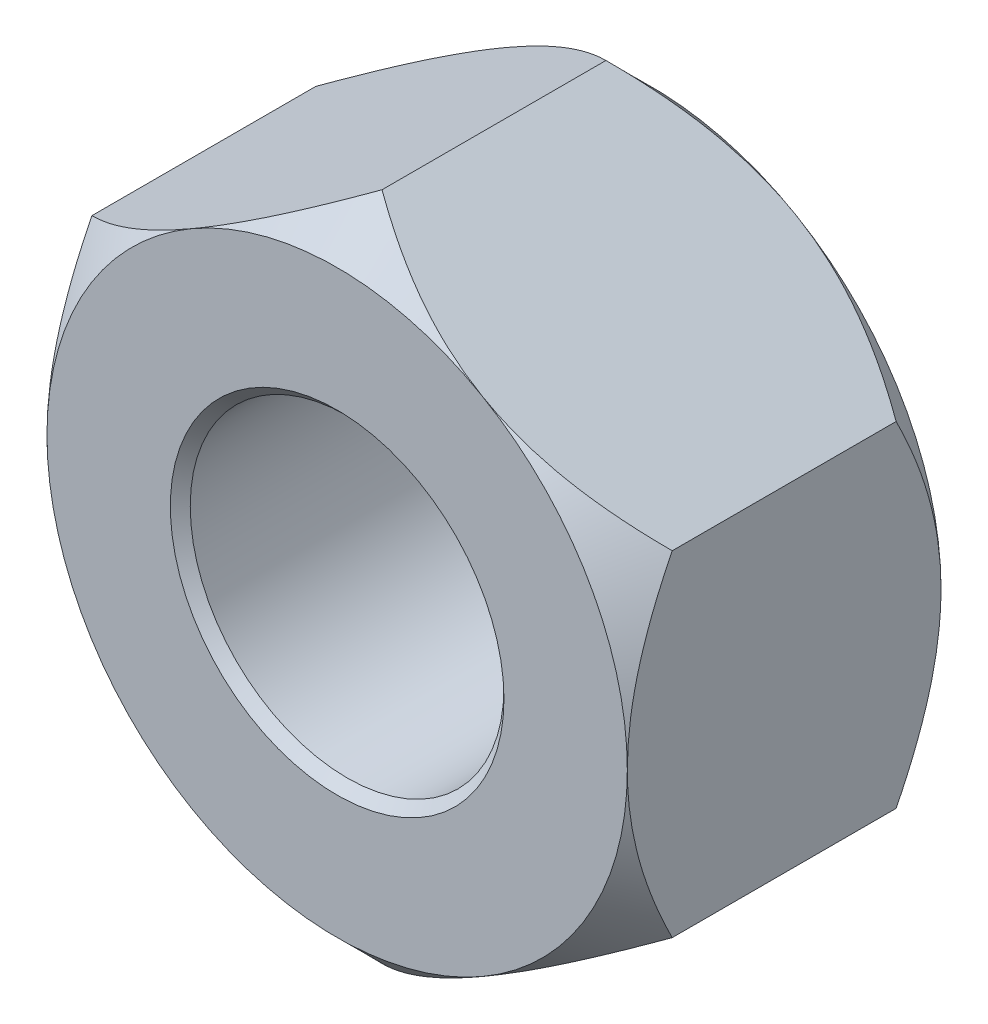
SolidWorks part; units mm, degrees
ref_plane "Front" through (0, 0, 0) normal (0, 0, 1) x (1, 0, 0)
ref_plane "Top" through (0, 0, 0) normal (0, 1, 0) x (1, 0, 0)
ref_plane "Right" through (0, 0, 0) normal (1, 0, 0) x (0, 0, -1)
sketch "Sketch1" plane through (0, 0, 0) normal (0, 0, 1) x (1, 0, 0)
  line L1 (0, -12.8172) -> (11.1, -6.4086)
  line L2 (11.1, -6.4086) -> (11.1, 6.4086)
  line L3 (11.1, 6.4086) -> (0, 12.8172)
  line L4 (0, 12.8172) -> (-11.1, 6.4086)
  line L5 (-11.1, 6.4086) -> (-11.1, -6.4086)
  line L6 (-11.1, -6.4086) -> (0, -12.8172)
  circle A0 centre (0, 0) radius 11.1 construction
  circle A1 centre (0, 0) radius 6
  dimension "Width" = 22.2
  dimension "ThreadDia" = 12
extrude "Boss-Extrude1" add sketch "Sketch1" along normal mid plane 12
sketch "Sketch4" plane through (0, 0, 6) normal (0, 0, 1) x (1, 0, 0)
  circle A0 centre (0, 0) radius 6.381
  circle A1 centre (0, 0) radius 6 construction
  dimension "D1" = 0.381
sketch "Sketch5" plane through (0, 0, -6) normal (0, 0, -1) x (-1, 0, 0)
  circle A1 centre (0, 0) radius 6.381
  circle A2 centre (0, 0) radius 6.381
  dimension "D1" = 0
extrude "Cut-Extrude3" cut sketch "Sketch4" against normal through all draft 45
extrude "Cut-Extrude4" cut sketch "Sketch5" against normal through all draft 45
sketch "Sketch6" plane through (0, 0, 6) normal (0, 0, 1) x (1, 0, 0)
  line L0 (-11.1, 0) -> (0, 0) construction
  line L2 (-11.1, 6.4086) -> (-11.1, -6.4086) construction
  circle A0 centre (0, 0) radius 11.1
extrude "Cut-Extrude5" cut sketch "Sketch6" against normal through all draft 45 flip side to cut
sketch "Sketch7" plane through (0, 0, -6) normal (0, 0, -1) x (-1, 0, 0)
  circle A1 centre (0, 0) radius 11.1
  circle A2 centre (0, 0) radius 11.1
  dimension "D1" = 0
extrude "Cut-Extrude6" cut sketch "Sketch7" against normal through all draft 45 flip side to cut
